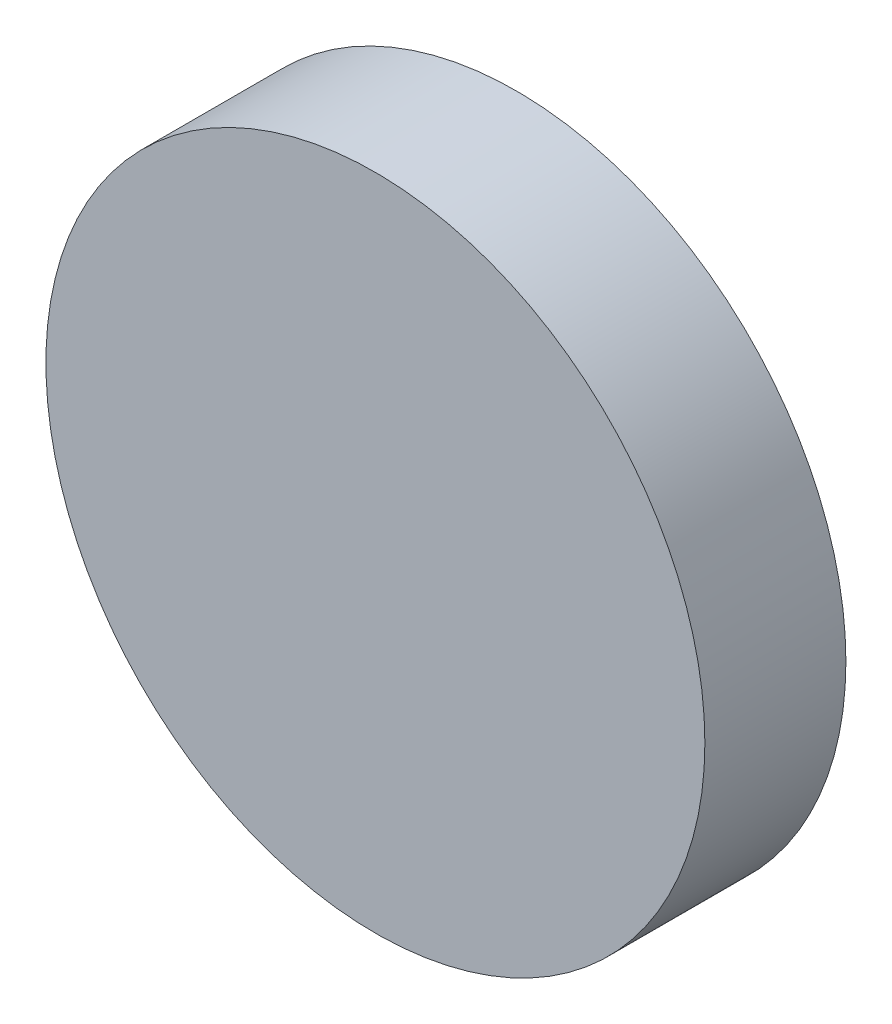
SolidWorks part; units mm, degrees
ref_plane "Front Plane" through (0, 0, 0) normal (0, 0, 1) x (1, 0, 0)
ref_plane "Top Plane" through (0, 0, 0) normal (0, 1, 0) x (1, 0, 0)
ref_plane "Right Plane" through (0, 0, 0) normal (1, 0, 0) x (0, 0, -1)
sketch "Model" plane through (0, 0, 0) normal (0, 0, 1) x (1, 0, 0)
  circle A0 centre (12.5, 12.5) radius 12.5
  dimension "D1" = 25
extrude "Boss-Extrude1" add sketch "Model" along normal blind 5.35
